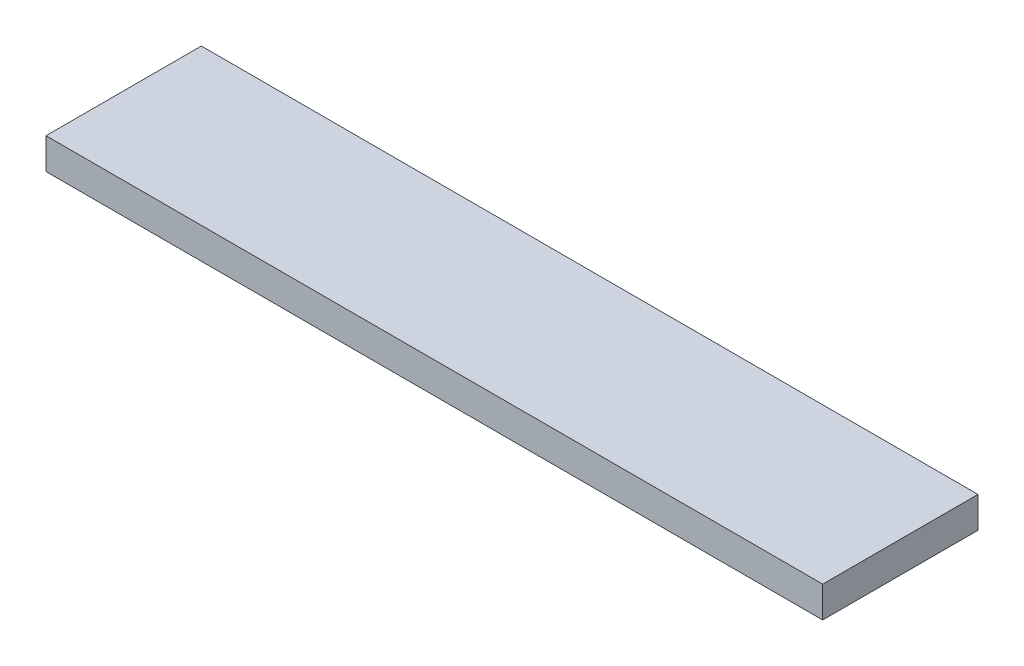
SolidWorks part; units mm, degrees
material "Pine"
ref_plane "Front Plane" through (0, 0, 0) normal (0, 0, 1) x (1, 0, 0)
ref_plane "Top Plane" through (0, 0, 0) normal (0, 1, 0) x (1, 0, 0)
ref_plane "Right Plane" through (0, 0, 0) normal (1, 0, 0) x (0, 0, -1)
sketch "Sketch1" plane through (0, 0, 0) normal (0, 1, 0) x (1, 0, 0)
  line L1 (-75, 15) -> (75, 15)
  line L2 (-75, 15) -> (-75, -15)
  line L3 (-75, -15) -> (75, -15)
  line L4 (75, 15) -> (75, -15)
  line L5 (-75, 15) -> (75, -15) construction
  line L6 (-75, -15) -> (75, 15) construction
  point P0 (0, 0)
  dimension "D1" = 150
  dimension "D2" = 30
extrude "Boss-Extrude1" add sketch "Sketch1" along normal blind 6
